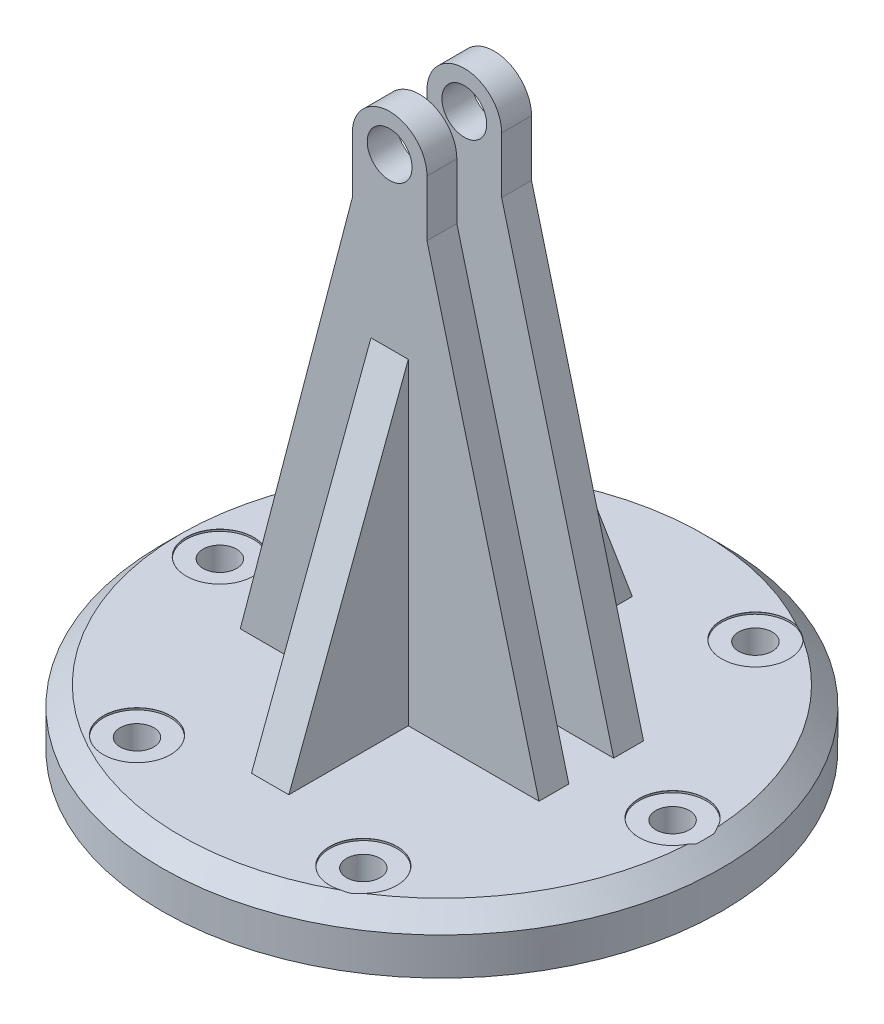
SolidWorks part; units mm, degrees
ref_plane "前视基准面" through (0, 0, 0) normal (0, 0, 1) x (1, 0, 0)
ref_plane "上视基准面" through (0, 0, 0) normal (0, 1, 0) x (1, 0, 0)
ref_plane "右视基准面" through (0, 0, 0) normal (1, 0, 0) x (0, 0, -1)
sketch "草图2" plane through (0, 0, 0) normal (0, 1, 0) x (1, 0, 0)
  circle A0 centre (0, 0) radius 75
  dimension "D1" = 150
extrude "凸台-拉伸1" add sketch "草图2" along normal blind 15
sketch "草图3" plane through (0, 0, 0) normal (0, 0, 1) x (1, 0, 0)
  line L0 (0, 0) -> (0, 150) construction
  line L1 (75, 15) -> (-75, 15) construction
  line L2 (10, 145) -> (10, 130)
  line L3 (-10, 145) -> (-10, 130)
  line L4 (10, 130) -> (40, 15)
  line L5 (-10, 130) -> (-40, 15)
  line L6 (-40, 15) -> (40, 15)
  circle A0 centre (0, 145) radius 6
  arc A1 (-10, 145) -> (10, 145) centre (0, 145) cw
  point P11 (40, 15)
  dimension "D2" = 12
  dimension "D4" = 10
  dimension "D1" = 150
  dimension "D3" = 130
  dimension "D5" = 15
  dimension "D6" = 40
extrude "凸台-拉伸2" add sketch "草图3" along normal mid plane 28
sketch "草图4" plane through (0, 0, 0) normal (1, 0, 0) x (0, 0, -1)
  line L0 (0, -4.7599) -> (0, 175.5825) construction
  line L1 (-14, 15) -> (14, 15) construction
  line L2 (-6, 15) -> (6, 15)
  line L3 (-6, 15) -> (-6, 165)
  line L4 (-6, 165) -> (6, 165)
  line L6 (6, 15) -> (6, 165)
  dimension "D1" = 150
  dimension "D2" = 12
extrude "切除-拉伸2" cut sketch "草图4" against normal through all both and the other way through all
sketch "草图5" plane through (0, 0, 0) normal (0, 1, 0) x (1, 0, 0)
  circle A0 centre (0, 0) radius 40
  dimension "D1" = 80
extrude "切除-拉伸3" cut sketch "草图5" along normal blind 7.5
chamfer "倒角2" distance 5 angle 45 1 edges at (0, 15, 75)
sketch "草图8" plane through (0, 0, 0) normal (1, 0, 0) x (0, 0, -1)
  line L0 (-14, 15) -> (-14, 130) construction
  line L1 (70, 15) -> (-70, 15) construction
  line L2 (-14, 100) -> (-46, 15)
  line L3 (70, 15) -> (-70, 15) construction
  line L4 (-14, 155) -> (-14, 145) construction
  point P0 (-14, 100)
  point P1 (-46, 15)
  dimension "D1" = 85
  dimension "D2" = 32
rib "筋21" sketch "草图8" sketch "草图8" thickness 10 extrusion direction parallel to sketch draft on no parameters "D1"=10
mirror "镜向1" about plane through (0, 0, 0) normal (0, 0, 1) of "筋21"
ref_plane "基准面5" through (0, 15, 0) normal (0, 1, 0) x (1, 0, 0)
sketch "草图23" plane through (0, 15, 0) normal (0, 1, 0) x (1, 0, 0)
  line L0 (0, 0) -> (-99.2426, 0) construction
hole_wizard "M8 六角头螺栓C级的柱形沉头孔7" positions "3D草图13" profile "草图24" counterbore size "M8" standard "GB" end condition through all
sketch3d "3D草图13"
  line L0 (0, 15, 0) -> (-99.2426, 15, 0) construction
  point P0 (-59.4777, 15, 0)
  dimension "D1" = 61.34
sketch "草图24" plane through (-59.4777, 15, 0) normal (1, 0, 0) x (0, 0, 1)
  line L0 (0, 0) -> (0, 15)
  line L1 (0, 15) -> (4.5, 15)
  line L3 (4.5, 15) -> (4.5, 0.5)
  line L4 (9, 0.5) -> (4.5, 0.5)
  line L5 (9, 0.5) -> (9, 0.021)
  line L6 (9, 0.021) -> (9.025, 0)
  line L7 (9.025, 0) -> (0, 0)
  line L8 (-9, 0.021) -> (-9.025, 0) construction
  line L11 (0, -6.35) -> (0, 107.95) construction
  dimension "通孔孔直径" = 9
  dimension "通孔孔深度" = 15
  dimension "柱形沉头孔直径" = 18
  dimension "柱形沉头孔深度" = 0.5
  dimension "近端锥形沉头孔直径" = 18.05
  dimension "近端锥形沉头孔角度" = 100
pattern_circular "阵列(圆周)3" count 6 over 360 about axis through (1.1514, 0, 0) along (0, 1, 0) of "M8 六角头螺栓C级的柱形沉头孔7"
